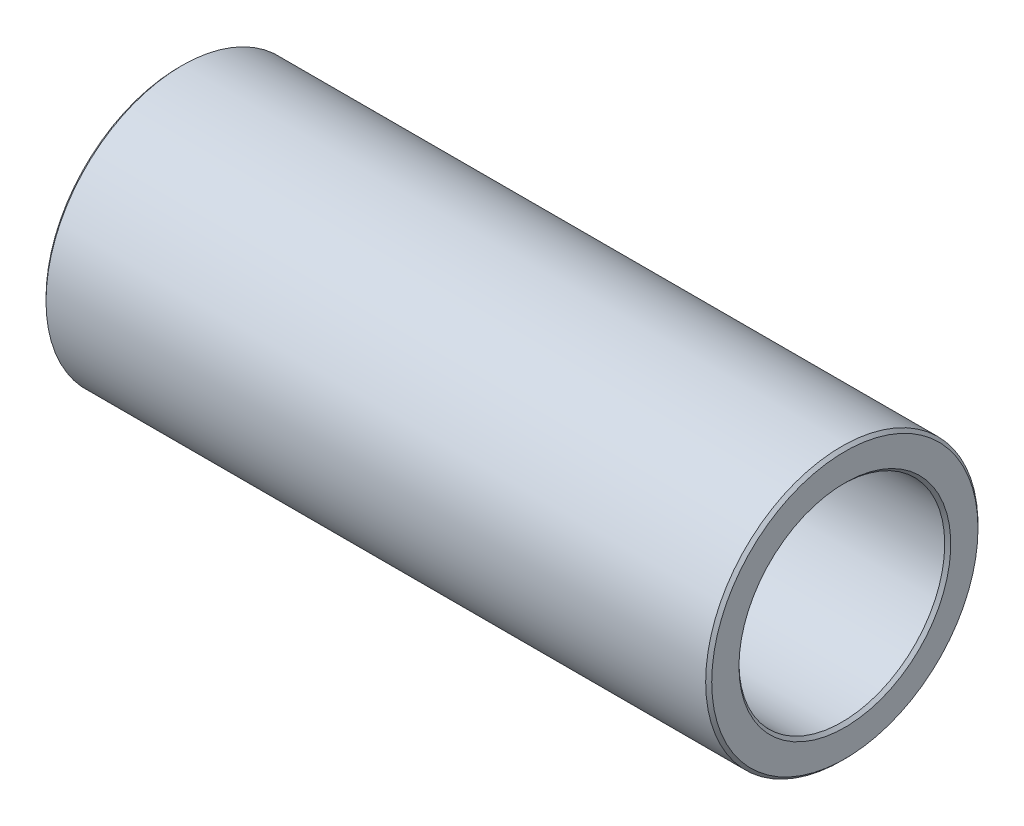
SolidWorks part; units mm, degrees
ref_plane "Front Plane" through (0, 0, 0) normal (0, 0, 1) x (1, 0, 0)
ref_plane "Top Plane" through (0, 0, 0) normal (0, 1, 0) x (1, 0, 0)
ref_plane "Right Plane" through (0, 0, 0) normal (1, 0, 0) x (0, 0, -1)
sketch "Sketch1" plane through (0, 0, 0) normal (0, 0, 1) x (1, 0, 0)
  line L0 (0, 0) -> (110, 0) construction
  line L1 (0, 22.5) -> (110, 22.5)
  line L2 (110, 22.5) -> (110, 17)
  line L3 (110, 17) -> (64, 17)
  line L4 (64, 17) -> (64, 12)
  line L7 (64, 12) -> (4, 12)
  line L8 (4, 12) -> (4, 9)
  line L9 (4, 9) -> (0, 9)
  line L10 (0, 9) -> (0, 22.5)
  dimension "D1" = 110
  dimension "D2" = 18
  dimension "D3" = 24
  dimension "D4" = 34
  dimension "D5" = 45
  dimension "D6" = 4
  dimension "D7" = 60
  dimension "D8" = 46
revolve "Revolve1" add sketch "Sketch1" angle 360 about L0
chamfer "Chamfer1" distance 0.5 angle 45 5 edges at (0, 0, 9) (0, 0, 22.5) (64, 0, 17) (110, 0, 17) (110, 0, 22.5)
